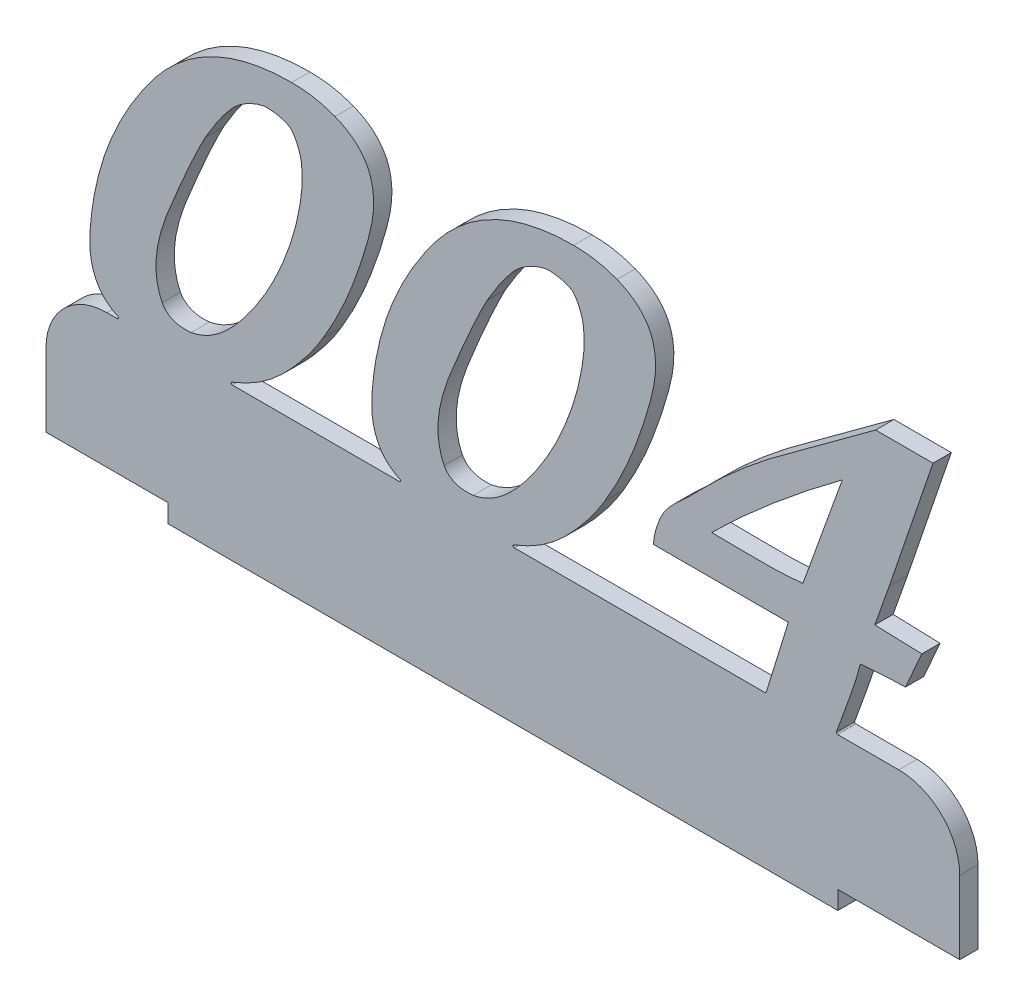
SolidWorks part; units mm, degrees
ref_plane "Front Plane" through (0, 0, 0) normal (0, 0, 1) x (1, 0, 0)
ref_plane "Top Plane" through (0, 0, 0) normal (0, 1, 0) x (1, 0, 0)
ref_plane "Right Plane" through (0, 0, 0) normal (1, 0, 0) x (0, 0, -1)
sketch "Sketch1" plane through (0, 0, 0) normal (0, 0, 1) x (1, 0, 0)
  line L0 (0, 20) -> (150, 20) construction
  line L1 (129.6705, 22) -> (150, 22)
  line L2 (0, 22) -> (0, 0)
  line L3 (0, 0) -> (20, 0)
  line L4 (150, 22) -> (150, 0)
  line L5 (0, 22) -> (12.808, 22)
  line L6 (143.781, 40.38) -> (141.0836, 34.3011)
  line L8 (118.1887, 22) -> (121.8694, 33.9101)
  line L9 (121.8694, 33.9101) -> (99.7036, 33.9101)
  line L10 (136.197, 68.4097) -> (145.6184, 68.4097)
  line L11 (130, 0) -> (150, 0)
  line L12 (145.6184, 68.4097) -> (138.4448, 47.3777)
  line L13 (20, 0) -> (20, -3)
  line L14 (20, -3) -> (130, -3)
  line L15 (130, 0) -> (130, -3)
  line L16 (138.4448, 47.3777) -> (136.0601, 40.6341)
  line L17 (136.0601, 40.6341) -> (143.781, 40.38)
  line L18 (29.4582, 22) -> (59.0942, 22)
  line L19 (75.7444, 22) -> (118.1887, 22)
  spline S0 degree 3 poles (40.1844, 63.269) (39.5832, 63.6785) (38.1179, 64.1847) (36.5801, 64.312) (35.7669, 64.2659) knots 0 0 0 0 0.469699 1 1 1 1
  spline S1 degree 3 poles (35.7669, 64.2659) (34.6222, 64.0252) (33.0042, 63.3477) (31.1158, 61.9701) (28.8079, 59.392) (27.2742, 56.9405) (26.1305, 54.9617) knots 0 0 0 0 0.25259 0.375811 0.50377 1 1 1 1
  spline S2 degree 3 poles (26.1305, 54.9617) (25.6742, 54.1637) (25.076, 52.8471) (24.1845, 51.0281) (23.471, 49.4465) (22.7066, 47.7273) (21.9062, 45.8605) (21.0496, 43.8643) (20.1775, 41.776) (19.3845, 39.6778) (18.7528, 37.6505) (18.312, 35.7434) (18.0691, 33.9504) (18.0218, 32.2711) (18.2235, 30.2454) (18.643, 28.8217) (19.0742, 27.968) knots 0 0 0 0 0.095871 0.150957 0.21155 0.277044 0.347448 0.42366 0.503899 0.583776 0.657815 0.725493 0.787949 0.846481 0.90051 1 1 1 1
  spline S3 degree 3 poles (19.0742, 27.968) (19.4327, 27.225) (20.9321, 26.0177) (22.845, 26.0011) (23.824, 26.072) knots 0 0 0 0 0.446154 1 1 1 1
  spline S4 degree 3 poles (23.824, 26.072) (25.2815, 26.3463) (27.4381, 27.3648) (29.9704, 29.5325) (31.9209, 31.6897) (33.7877, 34.1752) (35.5492, 36.8492) (37.1397, 39.6757) (38.5342, 42.632) (39.7323, 45.649) (40.7239, 48.661) (41.4426, 51.6495) (41.9471, 54.5401) (42.1167, 57.2419) (41.9148, 60.2724) (41.04, 62.261) (40.1844, 63.269) knots 0 0 0 0 0.099523 0.157976 0.224341 0.295662 0.367825 0.440561 0.514606 0.588508 0.65979 0.72866 0.796042 0.857776 0.911265 1 1 1 1
  spline S5 degree 3 poles (12.808, 22) (12.364, 22.1443) (11.4468, 22.4857) (10.2071, 23.2922) (9.0971, 24.3113) (8.2672, 25.5885) (7.6618, 27.0601) (7.1081, 29.4249) (7.1778, 31.3446) (7.2681, 32.6592) knots 0.510217 0.510217 0.510217 0.510217 0.5623 0.61932 0.674488 0.729675 0.788153 0.851799 1 1 1 1
  spline S6 degree 3 poles (7.2681, 32.6592) (7.435, 34.8873) (7.9242, 38.2128) (9.0536, 42.5496) (10.1164, 45.759) (11.4711, 48.8923) (13.0091, 51.9982) (14.8168, 55.0413) (16.8239, 58.0084) (19.0214, 60.7978) (21.4957, 63.2166) (24.1379, 65.3042) (27.0182, 66.9516) (30.0537, 68.2995) (34.4761, 69.5218) (37.9548, 69.9065) (40.3213, 69.8757) knots 0 0 0 0 0.122246 0.183381 0.245051 0.307032 0.370011 0.434579 0.500535 0.565958 0.62848 0.689454 0.749684 0.809559 0.870725 1 1 1 1
  spline S7 degree 3 poles (40.3213, 69.8757) (41.5815, 69.8653) (44.0244, 69.7218) (46.3645, 69.0119) (47.4558, 68.6052) knots 0 0 0 0 0.519885 1 1 1 1
  spline S8 degree 3 poles (47.4558, 68.6052) (48.7233, 68.0899) (50.5184, 67.0966) (52.2577, 65.1136) (53.1672, 63.4402) (53.6825, 61.5353) (53.8478, 59.4182) (53.6547, 57.0874) (52.9053, 53.748) (51.6268, 49.5816) (49.3256, 43.278) (47.1287, 38.8518) (45.462, 36.0993) knots 0 0 0 0 0.111906 0.162582 0.212593 0.265416 0.321766 0.384451 0.454781 0.599581 0.738515 1 1 1 1
  spline S9 degree 3 poles (45.462, 36.0993) (44.3705, 34.2421) (42.5002, 31.6717) (39.7509, 28.5487) (37.5822, 26.4794) (35.1997, 24.6717) (32.52, 23.176) (30.5528, 22.3763) (29.5023, 22.015) (29.4582, 22) knots 0 0 0 0 0.25786 0.380114 0.498337 0.616577 0.737567 0.865048 0.870621 0.870621 0.870621 0.870621
  spline S10 degree 3 poles (86.4706, 63.269) (85.8693, 63.6785) (84.4041, 64.1847) (82.8663, 64.312) (82.0531, 64.2659) knots 0 0 0 0 0.469699 1 1 1 1
  spline S11 degree 3 poles (82.0531, 64.2659) (80.9084, 64.0252) (79.2904, 63.3477) (77.402, 61.9701) (75.0941, 59.392) (73.5604, 56.9405) (72.4167, 54.9617) knots 0 0 0 0 0.25259 0.375811 0.50377 1 1 1 1
  spline S12 degree 3 poles (72.4167, 54.9617) (71.9604, 54.1637) (71.3622, 52.8471) (70.4706, 51.0281) (69.7572, 49.4465) (68.9928, 47.7273) (68.1923, 45.8605) (67.3357, 43.8643) (66.4637, 41.776) (65.6707, 39.6778) (65.039, 37.6505) (64.5982, 35.7434) (64.3553, 33.9504) (64.308, 32.2711) (64.5097, 30.2454) (64.9292, 28.8217) (65.3604, 27.968) knots 0 0 0 0 0.095871 0.150957 0.21155 0.277044 0.347448 0.42366 0.503899 0.583776 0.657815 0.725493 0.787949 0.846481 0.90051 1 1 1 1
  spline S13 degree 3 poles (65.3604, 27.968) (65.7188, 27.225) (67.2183, 26.0177) (69.1312, 26.0011) (70.1102, 26.072) knots 0 0 0 0 0.446154 1 1 1 1
  spline S14 degree 3 poles (70.1102, 26.072) (71.5677, 26.3463) (73.7243, 27.3648) (76.2566, 29.5325) (78.2071, 31.6897) (80.0739, 34.1752) (81.8354, 36.8492) (83.4258, 39.6757) (84.8204, 42.632) (86.0185, 45.649) (87.01, 48.661) (87.7287, 51.6495) (88.2333, 54.5401) (88.4029, 57.2419) (88.201, 60.2724) (87.3262, 62.261) (86.4706, 63.269) knots 0 0 0 0 0.099523 0.157976 0.224341 0.295662 0.367825 0.440561 0.514606 0.588508 0.65979 0.72866 0.796042 0.857776 0.911265 1 1 1 1
  spline S15 degree 3 poles (59.0942, 22) (58.6502, 22.1443) (57.733, 22.4857) (56.4932, 23.2922) (55.3833, 24.3113) (54.5534, 25.5885) (53.9479, 27.0601) (53.3943, 29.4249) (53.4639, 31.3446) (53.5543, 32.6592) knots 0.510217 0.510217 0.510217 0.510217 0.5623 0.61932 0.674488 0.729675 0.788153 0.851799 1 1 1 1
  spline S16 degree 3 poles (53.5543, 32.6592) (53.7212, 34.8873) (54.2104, 38.2128) (55.3398, 42.5496) (56.4026, 45.759) (57.7572, 48.8923) (59.2952, 51.9982) (61.103, 55.0413) (63.11, 58.0084) (65.3076, 60.7978) (67.7818, 63.2166) (70.4241, 65.3042) (73.3043, 66.9516) (76.3398, 68.2995) (80.7622, 69.5218) (84.241, 69.9065) (86.6074, 69.8757) knots 0 0 0 0 0.122246 0.183381 0.245051 0.307032 0.370011 0.434579 0.500535 0.565958 0.62848 0.689454 0.749684 0.809559 0.870725 1 1 1 1
  spline S17 degree 3 poles (86.6074, 69.8757) (87.8677, 69.8653) (90.3105, 69.7218) (92.6507, 69.0119) (93.7419, 68.6052) knots 0 0 0 0 0.519885 1 1 1 1
  spline S18 degree 3 poles (93.7419, 68.6052) (95.0095, 68.0899) (96.8045, 67.0966) (98.5438, 65.1136) (99.4534, 63.4402) (99.9686, 61.5353) (100.1339, 59.4182) (99.9408, 57.0874) (99.1914, 53.748) (97.9129, 49.5816) (95.6117, 43.278) (93.4148, 38.8518) (91.7482, 36.0993) knots 0 0 0 0 0.111906 0.162582 0.212593 0.265416 0.321766 0.384451 0.454781 0.599581 0.738515 1 1 1 1
  spline S19 degree 3 poles (91.7482, 36.0993) (90.6567, 34.2421) (88.7864, 31.6717) (86.037, 28.5487) (83.8683, 26.4794) (81.4859, 24.6717) (78.8062, 23.176) (76.839, 22.3763) (75.7884, 22.015) (75.7444, 22) knots 0 0 0 0 0.25786 0.380114 0.498337 0.616577 0.737567 0.865048 0.870621 0.870621 0.870621 0.870621
  spline S20 degree 3 poles (130.7239, 58.5778) (126.7671, 55.6511) (119.397, 49.8355) (112.455, 43.5149) (109.2814, 40.38) knots 0 0 0 0 0.524587 1 1 1 1
  spline S21 degree 3 poles (109.2814, 40.38) (111.7778, 40.4164) (116.7694, 40.2159) (121.7677, 40.3592) (124.254, 40.6341) knots 0 0 0 0 0.499666 1 1 1 1
  spline S22 degree 3 poles (124.254, 40.6341) (125.3599, 43.6268) (127.4482, 49.6325) (129.6306, 55.6046) (130.7239, 58.5778) knots 0 0 0 0 0.501754 1 1 1 1
  spline S23 degree 3 poles (141.0836, 34.3011) (140.0465, 34.3099) (137.582, 34.1892) (135.1198, 34.0394) (133.695, 33.9101) knots 0 0 0 0 0.420206 1 1 1 1
  spline S24 degree 3 poles (133.695, 33.9101) (133.1826, 31.8232) (132.1382, 28.782) (130.6941, 24.8466) (129.996, 22.9231) (129.6705, 22) knots 0 0 0 0 0.502209 0.752081 0.981127 0.981127 0.981127 0.981127
  spline S25 degree 2 poles (99.7036, 33.9101) (99.8304, 35.6923) (100.505, 37.3503) knots 0 0 0 1 1 1
  spline S26 degree 3 poles (100.505, 37.3503) (100.756, 38.1545) (101.3491, 39.2839) (102.3961, 40.6576) (104.471, 42.6867) (106.3368, 44.3024) (107.6981, 45.7944) knots 0 0 0 0 0.224443 0.338858 0.460951 1 1 1 1
  spline S27 degree 3 poles (107.6981, 45.7944) (109.8155, 47.9817) (113.2283, 51.1468) (118.1239, 55.1483) (122.0739, 58.0824) (125.9919, 60.9038) (130.6955, 64.3361) (134.0652, 66.8105) (136.197, 68.4097) knots 0 0 0 0 0.250612 0.382932 0.520503 0.655731 0.780544 1 1 1 1
  dimension "D1" = 150
  dimension "D2" = 3
  dimension "D3" = 20
  dimension "D4" = 20
  dimension "D5" = 20
extrude "Boss-Extrude1" add sketch "Sketch1" along normal blind 3
fillet "Fillet1" radius 10 2 edges at (0, 22, 1.5) (150, 22, 1.5)
fillet "Fillet2" radius 0.2 6 edges at (59.0942, 22, 1.5) (118.1887, 22, 1.5) (12.808, 22, 1.5) (129.6705, 22, 1.5) (75.7444, 22, 1.5) (29.4582, 22, 1.5)
